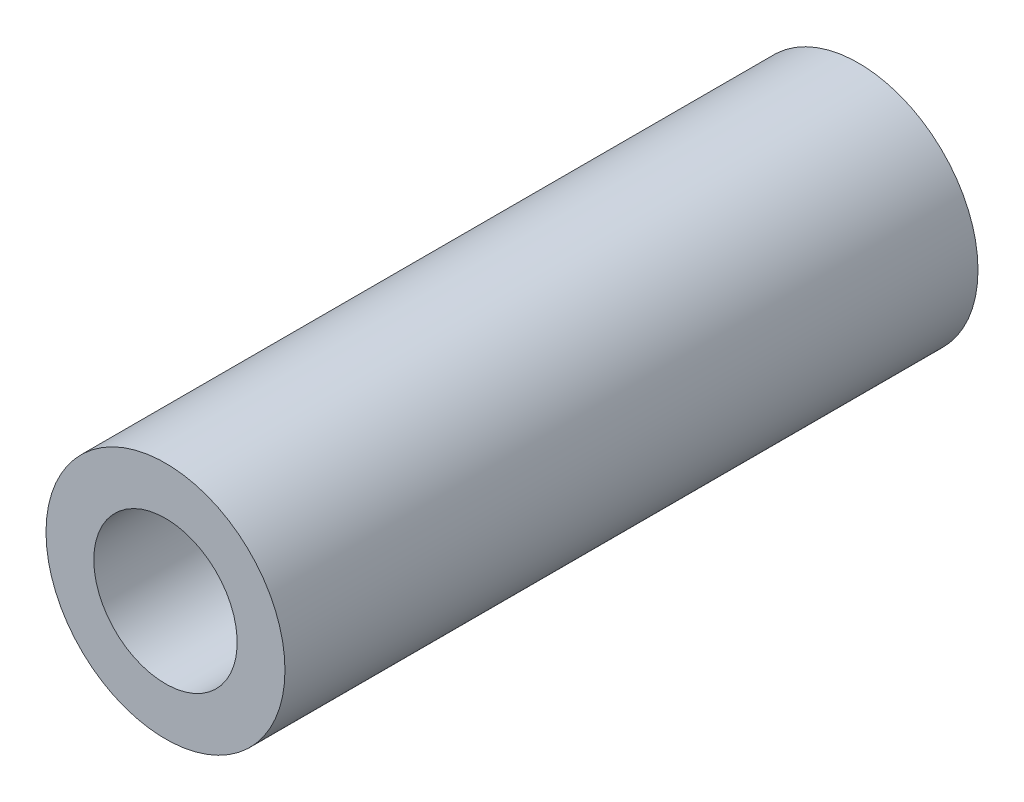
SolidWorks part; units mm, degrees
material "ABS PC"
ref_plane "前视基准面" through (0, 0, 0) normal (0, 0, 1) x (1, 0, 0)
ref_plane "上视基准面" through (0, 0, 0) normal (0, 1, 0) x (1, 0, 0)
ref_plane "右视基准面" through (0, 0, 0) normal (1, 0, 0) x (0, 0, -1)
sketch "草图1" plane through (0, 0, 0) normal (0, 0, 1) x (1, 0, 0)
  circle A0 centre (0, 0) radius 3
  circle A1 centre (0, 0) radius 5
extrude "凸台-拉伸1" add sketch "草图1" along normal blind 29
